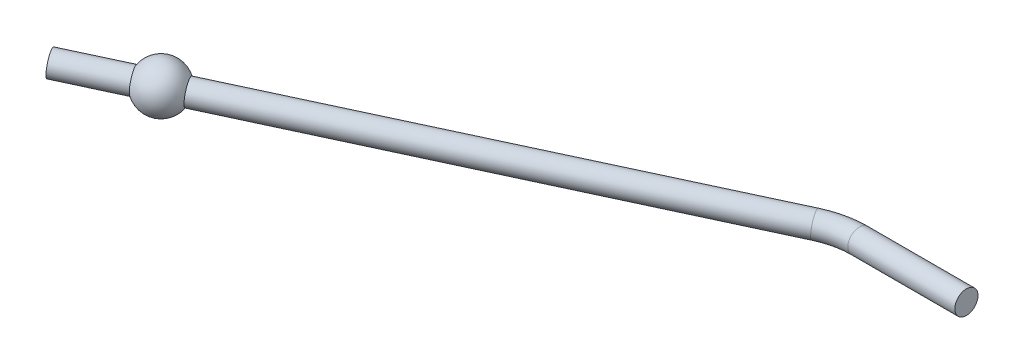
SolidWorks part; units mm, degrees
material "AISI 1020"
ref_plane "Front Plane" through (0, 0, 0) normal (0, 0, 1) x (1, 0, 0)
ref_plane "Top Plane" through (0, 0, 0) normal (0, 1, 0) x (1, 0, 0)
ref_plane "Right Plane" through (0, 0, 0) normal (1, 0, 0) x (0, 0, -1)
sketch3d "3DSketch1"
  line L0 (-68.6428, 4.2237, 31.6927) -> (-15.5579, 0.1369, 1.0273)
  line L1 (-11.7211, 0, 0) -> (0, 0, 0)
  line L3 (-13.7795, 0, 0) -> (-13.7795, 1.905, 0) construction
  line L4 (-68.6428, 4.2237, 31.6927) -> (-68.9402, 5.9515, 30.9476) construction
  circle A0 centre (-68.6428, 4.2237, 31.6927) radius 1.905 construction
  circle A1 centre (-13.7795, 0, 0) radius 1.905 construction
  arc A2 (-15.5579, 0.1369, 1.0273) -> (-11.7211, 0, 0) centre (-11.7211, 1.0066, 7.5532) ccw
  point P2 (-11.8745, 0, 0)
  point P3 (0, 0, 0)
  point P7 (-67.0169, 4.8393, 32.4715)
  point P8 (0, 0, 0)
  point P10 (-58.4185, 3.4764, 27.8563)
  point P11 (-59.6614, 4.9919, 25.4)
  point P16 (-13.7795, 0, 0)
  point P18 (-11.7211, -6.5466, 8.5598)
  dimension "D4" = 86.186
  dimension "D5" = 3.81
  dimension "D6" = 3.81
  dimension "D7" = 7.62
  dimension "D1" = 13.7795
  dimension "D2" = 63.5
  dimension "D3" = 149.767
ref_plane "Plane1" through (-68.6428, 4.2237, 31.6927) normal (0.864, -0.0665, -0.4991) x (-0.4976, 0.0383, -0.8665)
sketch "Sketch1" plane through (-68.6428, 4.2237, 31.6927) normal (0.864, -0.0665, -0.4991) x (-0.4976, 0.0383, -0.8665)
  circle A0 centre (0, 0) radius 1.27
  dimension "D1" = 2.54
sweep "Sweep1" add profiles "Sketch1" path "3DSketch1"
ref_plane "Plane2" through (-60.9619, 3.6323, 27.2557) normal (0.864, -0.0665, -0.4991) x (-0.4976, 0.0383, -0.8665)
sketch "Sketch2" plane through (-60.9619, 3.6323, 27.2557) normal (0.864, -0.0665, -0.4991) x (-0.4976, 0.0383, -0.8665)
  line L0 (0, 2.54) -> (0, -2.54)
  arc A0 (0, -2.54) -> (0, 2.54) centre (0, 0) ccw
  dimension "D1" = 5.08
revolve "Revolve1" add sketch "Sketch2" angle 360 about L0
